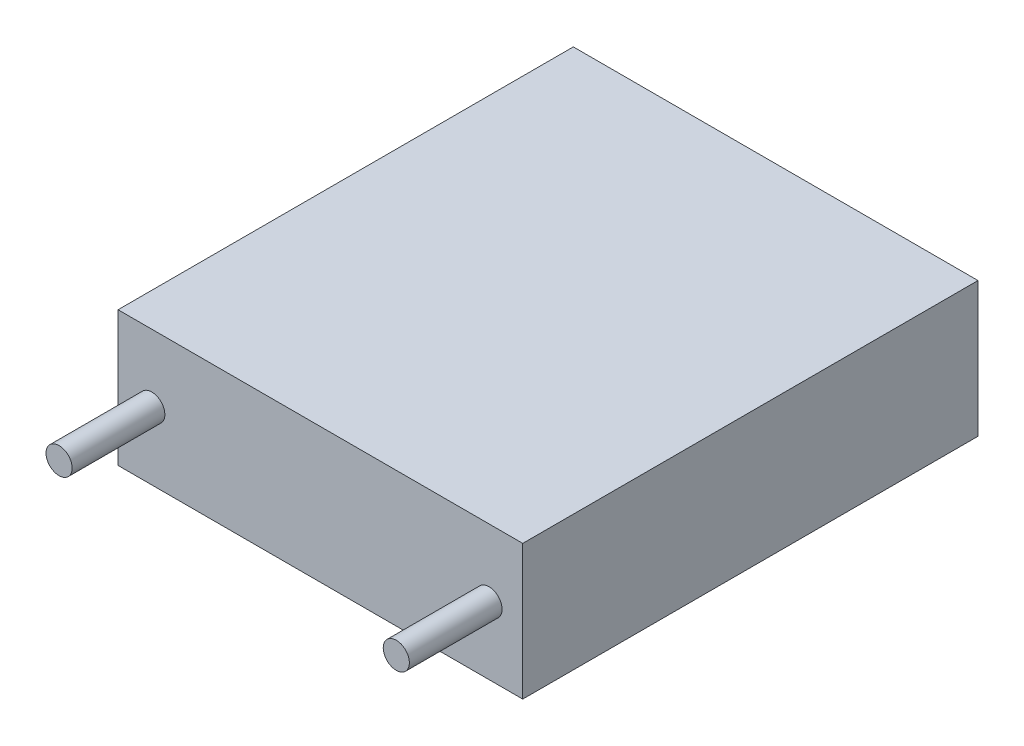
SolidWorks part; units mm, degrees
ref_plane "Спереди" through (0, 0, 0) normal (0, 0, 1) x (1, 0, 0)
ref_plane "Сверху" through (0, 0, 0) normal (0, 1, 0) x (1, 0, 0)
ref_plane "Справа" through (0, 0, 0) normal (1, 0, 0) x (0, 0, -1)
sketch "Эскиз1" plane through (0, 0, 0) normal (0, 0, 1) x (1, 0, 0)
  line L1 (0, 0) -> (24, 0)
  line L2 (0, 0) -> (0, 8)
  line L3 (0, 8) -> (24, 8)
  line L4 (24, 0) -> (24, 8)
  dimension "D1" = 8
  dimension "D2" = 24
extrude "Вытянуть1" add sketch "Эскиз1" along normal blind 27
sketch "Эскиз2" plane through (0, 0, 27) normal (0, 0, 1) x (1, 0, 0)
  line L0 (-0.6613, 4) -> (24.2043, 4) construction
  line L1 (0, 0) -> (24, 0) construction
  line L2 (24, 8) -> (0, 8) construction
  line L3 (12, 10.4113) -> (12, -0.9059) construction
  line L4 (0, 8) -> (0, 0) construction
  line L5 (24, 0) -> (24, 8) construction
  circle A0 centre (2, 4) radius 0.7746
  circle A1 centre (22, 4) radius 0.7746
  dimension "D1" = 20
extrude "Вытянуть2" add sketch "Эскиз2" along normal blind 5.5
